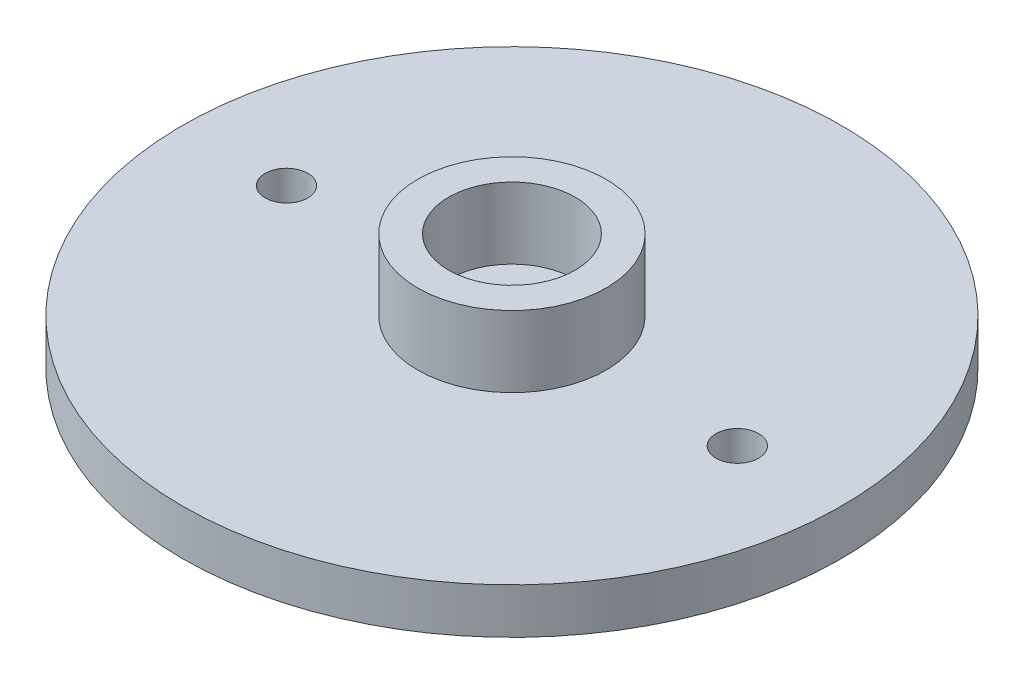
SolidWorks part; units mm, degrees
material "Pure Silver"
ref_plane "Front Plane" through (0, 0, 0) normal (0, 0, 1) x (1, 0, 0)
ref_plane "Top Plane" through (0, 0, 0) normal (0, 1, 0) x (1, 0, 0)
ref_plane "Right Plane" through (0, 0, 0) normal (1, 0, 0) x (0, 0, -1)
sketch "Sketch1" plane through (0, 0, 0) normal (0, 1, 0) x (1, 0, 0)
  circle A0 centre (0, 0) radius 11.7729
  circle A1 centre (0, 0) radius 1.016
  dimension "D1" = 23.5458
  dimension "D2" = 2.032
extrude "Boss-Extrude1" add sketch "Sketch1" along normal blind 1.6256
sketch "Sketch2" plane through (0, 1.6256, 0) normal (0, 1, 0) x (1, 0, 0)
  line L0 (0, 0) -> (8.0518, 0) construction
  line L1 (-8.0518, 0) -> (0, 0) construction
  circle A0 centre (8.0518, 0) radius 0.762
  circle A1 centre (-8.0518, 0) radius 0.762
  dimension "D2" = 1.524
  dimension "D1" = 16.1036
extrude "Cut-Extrude1" cut sketch "Sketch2" against normal through all
sketch "Sketch3" plane through (0, 1.6256, 0) normal (0, 1, 0) x (1, 0, 0)
  circle A0 centre (0, 0) radius 3.3655
  circle A1 centre (0, 0) radius 2.2606
  dimension "D1" = 6.731
  dimension "D2" = 4.5212
extrude "Boss-Extrude2" add sketch "Sketch3" along normal blind 2.54
sketch "Sketch4" plane through (0, 0, 0) normal (0, -1, 0) x (1, 0, 0)
  circle A0 centre (0, 0) radius 2.6924
  dimension "D1" = 5.3848
extrude "Boss-Extrude3" add sketch "Sketch4" along normal blind 0.8636
sketch "Sketch5" plane through (0, -0.8636, 0) normal (0, -1, 0) x (1, 0, 0)
  circle A0 centre (0, 0) radius 2.2606
  dimension "D1" = 4.5212
extrude "Cut-Extrude2" cut sketch "Sketch5" against normal blind 1.27
